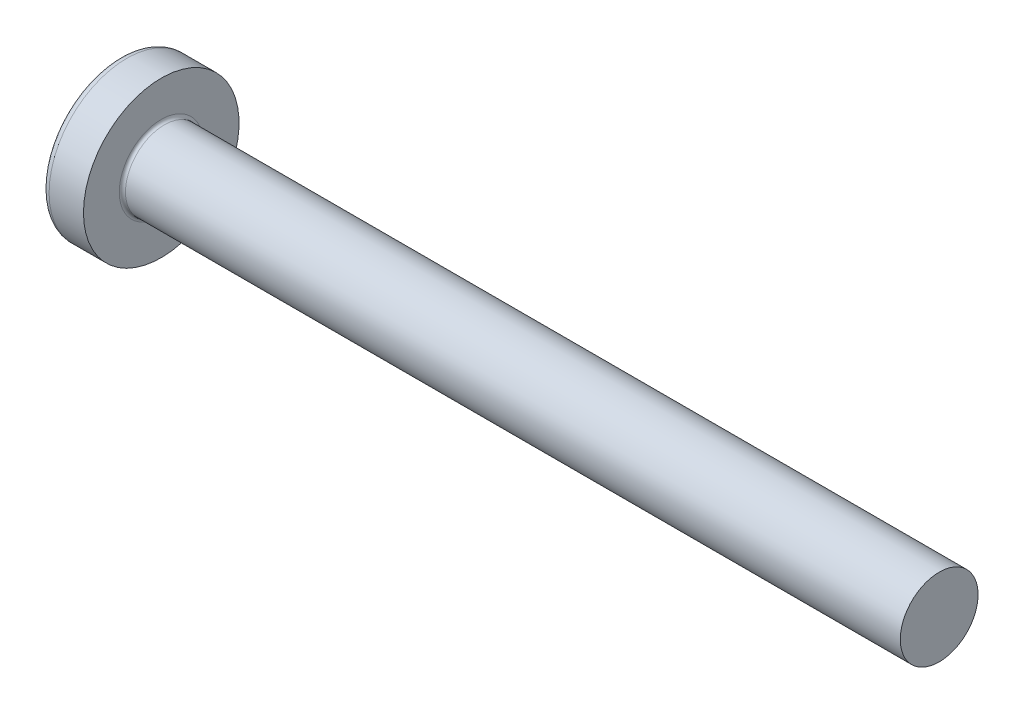
SolidWorks part; units mm, degrees
ref_plane "Plane1" through (0, 0, 0) normal (0, 0, 1) x (1, 0, 0)
ref_plane "Plane2" through (0, 0, 0) normal (0, 1, 0) x (1, 0, 0)
ref_plane "Plane3" through (0, 0, 0) normal (1, 0, 0) x (0, 0, -1)
sketch "BodySke" plane through (0, 0, 0) normal (0, 0, 1) x (1, 0, 0)
  line L0 (2.1, 1.25) -> (2.1, 2.5)
  line L1 (2.325, 6.35) -> (2.325, -3.175) construction
  line L2 (-25.4, 0) -> (127, 0) construction
  line L3 (27.1, 0) -> (0, 0)
  line L4 (2.1, 1.25) -> (27.1, 1.25)
  line L5 (27.1, 1.25) -> (27.1, 0)
  line L6 (0.995, 2.5) -> (2.1, 2.5)
  line L8 (2.1, 6.35) -> (2.1, -3.175) construction
  arc A0 (0.8032, 2.4043) -> (0, 0) centre (4, 0) ccw
  arc A2 (0.8032, 2.4043) -> (0.995, 2.5) centre (0.995, 2.26) cw
  dimension "Head_fillet_rad" = 0.24
  dimension "Head_crown_rad" = 4
  dimension "Head_ht" = 2.1
  dimension "Diameter" = 2.5
  dimension "Length" = 25
  dimension "Head_dia" = 5
  dimension "Advance" = 0.45
  dimension "Thread_nom" = 25
revolve "Base-Revolve" add sketch "BodySke"
cosmetic thread "ThreadCosmetic" [suppressed]
fillet "Fillet1" radius 0.1 1 edges at (2.1, 0, 1.25)
sketch "Sketch3" plane through (0, 0, 0) normal (1, 0, 0) x (0, 0, -1)
  line L0 (0.37, -1.3) -> (-0.37, -1.3)
  line L1 (0.37, -1.3) -> (0.37, 1.3)
  line L2 (-0.37, 1.3) -> (0.37, 1.3)
  line L3 (-0.37, 1.3) -> (-0.37, -1.3)
  dimension "D1" = 1.3
  dimension "Cross_dia" = 2.6
  dimension "D2" = 0.37
  dimension "Cross_width" = 0.74
ref_plane "Plane4" through (1.5, 0, 0) normal (1, 0, 0) x (0, 0, -1)
sketch "Sketch4" plane through (1.5, 0, 0) normal (1, 0, 0) x (0, 0, -1)
  line L0 (0.37, -0.5521) -> (-0.37, -0.5521)
  line L1 (0.37, -0.5521) -> (0.37, 0.5521)
  line L2 (-0.37, 0.5521) -> (0.37, 0.5521)
  line L3 (-0.37, 0.5521) -> (-0.37, -0.5521)
  dimension "D1" = 0.74
  dimension "D2" = 1.1043
  dimension "D3" = 0.37
  dimension "D4" = 0.5521
loft "Recess" cut profiles "Sketch3", "Sketch4"
pattern_circular "RecPat" count 2 every 90 about axis through (0, 0, 0) along (1, 0, 0) of "Recess"
sketch "RecCorSke" plane through (0, 0, 0) normal (0, 0, 1) x (1, 0, 0)
  line L0 (-3.175, 0) -> (15.875, 0) construction
  line L1 (-25.4, 0) -> (127, 0) construction
  line L2 (0, 0) -> (0, 0.6609)
  line L3 (0, 0.6609) -> (1.5, 0.556)
  line L4 (1.5, 0.556) -> (1.6807, 0)
  line L5 (1.6807, 0) -> (0, 0)
  dimension "Diameter" = 1.112
  dimension "Depth" = 1.5
  dimension "Draft_angle" = 4
  dimension "Bottom_angle" = 18
revolve "RecessCore" cut sketch "RecCorSke" angle 360 about L0
sketch "ThdSchSke" plane through (0, 0, 0) normal (0, 0, 1) x (1, 0, 0)
  line L0 (3, -0.9965) -> (2.8225, -1.25)
  line L1 (3, -0.9965) -> (3.1775, -1.25)
  line L2 (3.1775, -1.25) -> (3.1775, -1.5625)
  line L3 (-3.175, 0) -> (5.1513, 0) construction
  line L5 (3.1775, -1.5625) -> (2.8225, -1.5625)
  line L6 (2.8225, -1.5625) -> (2.8225, -1.25)
  dimension "Thread_minor" = 1.993
  dimension "Diameter" = 2.5
  dimension "Start" = 3
  dimension "SideAngle" = 55
  dimension "VeeAngle" = 70
  dimension "Overcut" = 3.125
revolve "ThreadSchematic" [suppressed] cut sketch "ThdSchSke" angle 360 about L3
pattern_linear "ThdSchPat" [suppressed]
equation "\"D1@Sketch3\" = \"Cross_dia@Sketch3\" / 2"
equation "\"D2@Sketch3\" = \"Cross_width@Sketch3\" / 2"
equation "\"Depth@RecCorSke\" = \"Cross_depth@Plane4\""
equation "\"D1@Sketch4\" = \"Cross_width@Sketch3\""
equation "\"D2@Sketch4\" = \"Cross_dia@Sketch3\" - 2.0 * \"Cross_depth@Plane4\" * tan(26.5  * 0.017453292)"
equation "\"D3@Sketch4\" = \"D1@Sketch4\" / 2"
equation "\"D4@Sketch4\" = \"D2@Sketch4\" / 2"
equation "\"Thread_length@ThreadCosmetic\" = ((sgn( (\"Length@BodySke\" - \"Advance@BodySke\" * 2.0 ) - \"Thread_nom@BodySke\" )-1)*( (\"Length@BodySke\" - \"Advance@BodySke\" * 2.0 ) - \"Thread_nom@BodySke\" ))/-2+ \"Thread_nom@BodySke\""
equation "\"Thread_minor@ThdSchSke\" = \"Thread_minor@ThreadCosmetic\""
equation "\"Diameter@ThdSchSke\" = \"Diameter@BodySke\""
equation "\"Overcut@ThdSchSke\" = \"Diameter@BodySke\" * 1.25"
equation "\"Start@ThdSchSke\" = \"Head_ht@BodySke\" + \"Length@BodySke\" - \"Thread_length@ThreadCosmetic\"  '---Non-countersunk---"
equation "\"Num_threads@ThdSchPat\" = int( \"Thread_length@ThreadCosmetic\" / \"Advance@BodySke\" + 0.999 )  + 1"
equation "\"Advance@ThdSchPat\" = \"Thread_length@ThreadCosmetic\" /  (\"Num_threads@ThdSchPat\" - 1) 'relax it"
